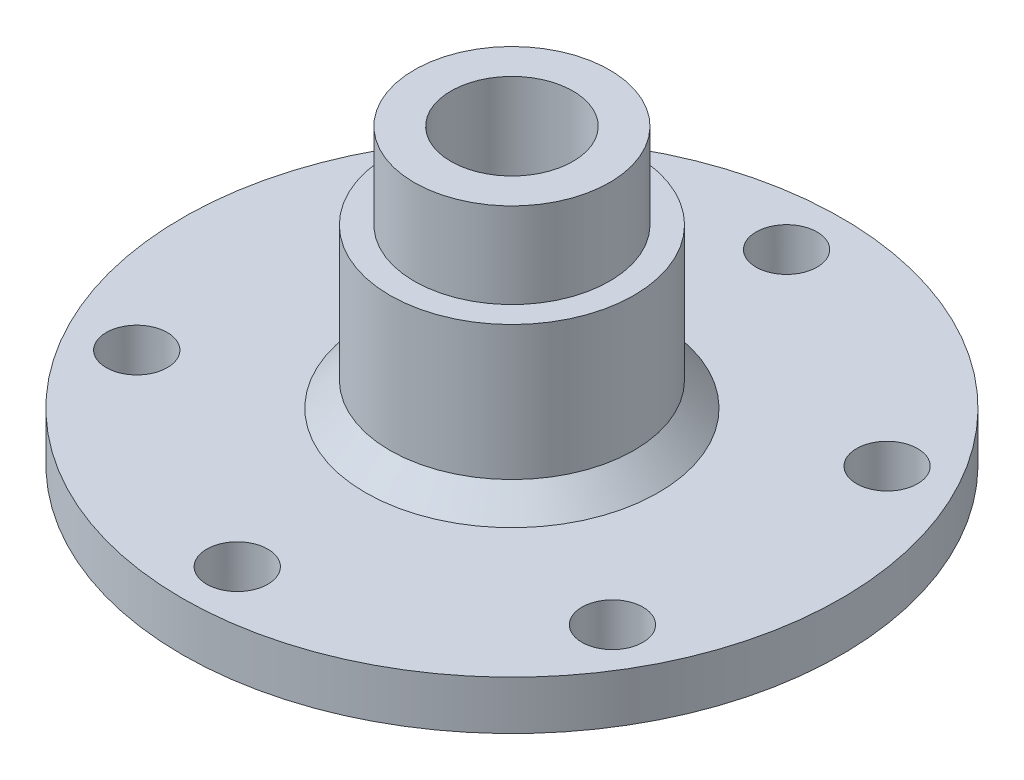
SolidWorks part; units mm, degrees
material "6061 合金"
ref_plane "前视基准面" through (0, 0, 0) normal (0, 0, 1) x (1, 0, 0)
ref_plane "上视基准面" through (0, 0, 0) normal (0, 1, 0) x (1, 0, 0)
ref_plane "右视基准面" through (0, 0, 0) normal (1, 0, 0) x (0, 0, -1)
sketch "草图1" plane through (0, 0, 0) normal (0, 0, 1) x (1, 0, 0)
  line L0 (0, 0) -> (0, -8.0562) construction
  line L1 (-10, 2) -> (-27, 2)
  line L2 (-27, 2) -> (-27, 6)
  line L3 (-27, 6) -> (-10, 6)
  line L4 (-10, 6) -> (-10, 19)
  line L5 (-10, 19) -> (-8, 19)
  line L6 (-8, 19) -> (-8, 26)
  line L7 (-8, 26) -> (-5, 26)
  line L8 (-5, 26) -> (-5, 0)
  line L9 (-10, 2) -> (-10, 0)
  line L10 (-10, 0) -> (-5, 0)
  dimension "D1" = 10
  dimension "D2" = 16
  dimension "D3" = 20
  dimension "D4" = 54
  dimension "D5" = 4
  dimension "D6" = 17
  dimension "D7" = 7
  dimension "D8" = 2
revolve "旋转1" add sketch "草图1" angle 360 about L0
sketch "草图2" plane through (0, 2, 0) normal (0, -1, 0) x (1, 0, 0)
  circle A0 centre (0, 0) radius 22.5 construction
  circle A1 centre (0, 22.5) radius 2.5
  circle A2 centre (19.4856, 11.25) radius 2.5
  circle A3 centre (19.4856, -11.25) radius 2.5
  circle A4 centre (0, -22.5) radius 2.5
  circle A5 centre (-19.4856, -11.25) radius 2.5
  circle A6 centre (-19.4856, 11.25) radius 2.5
  point P18 (0, 0)
  dimension "D1" = 45
  dimension "D2" = 5
  dimension "D3" = 6
extrude "切除-拉伸2" cut sketch "草图2" against normal blind 10
chamfer "倒角1" distance 2 angle 45 1 edges at (0, 6, 10)
scale "缩放比例1" bodies to scale 102 scale about origin uniform scaling yes scale factor 0.8
scale "缩放比例2" bodies to scale 105 scale about origin uniform scaling yes scale factor 0.8
scale "缩放比例3" scale about origin uniform scaling yes scale factor 0.8
